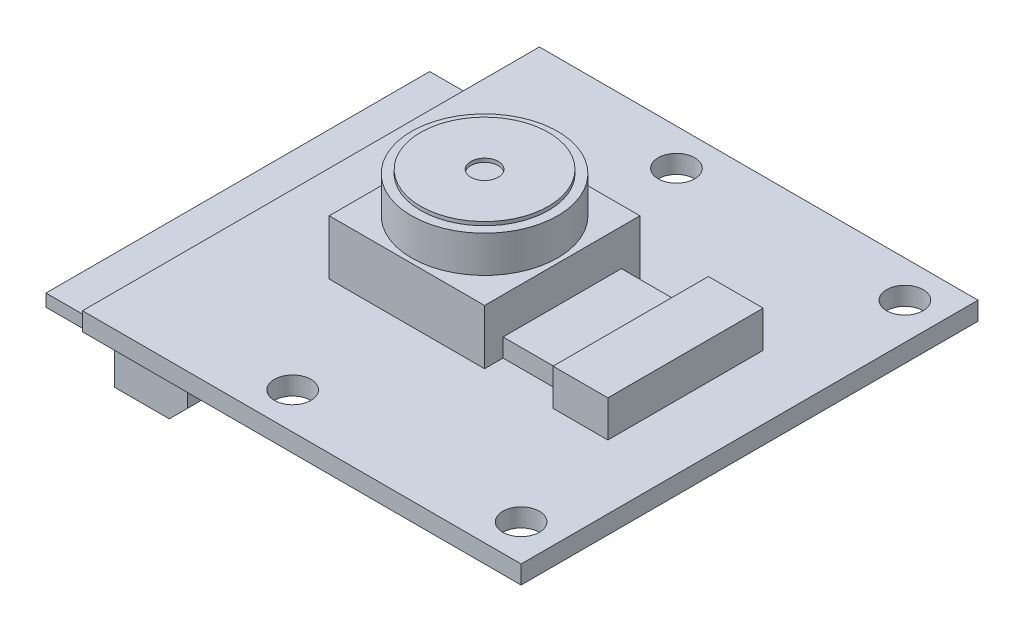
SolidWorks part; units mm, degrees
ref_plane "前视基准面" through (0, 0, 0) normal (0, 0, 1) x (1, 0, 0)
ref_plane "上视基准面" through (0, 0, 0) normal (0, 1, 0) x (1, 0, 0)
ref_plane "右视基准面" through (0, 0, 0) normal (1, 0, 0) x (0, 0, -1)
sketch "草图1" plane through (0, 0, 0) normal (0, 1, 0) x (1, 0, 0)
  line L1 (-12, 12.5) -> (12, 12.5)
  line L2 (-12, 12.5) -> (-12, -12.5)
  line L3 (-12, -12.5) -> (12, -12.5)
  line L4 (12, 12.5) -> (12, -12.5)
  line L5 (-12, 12.5) -> (12, -12.5) construction
  line L6 (-12, -12.5) -> (12, 12.5) construction
  point P0 (0, 0)
  dimension "D1" = 24
  dimension "D2" = 25
extrude "凸台-拉伸1" add sketch "草图1" along normal blind 1
sketch "草图2" plane through (0, 1, 0) normal (0, 1, 0) x (1, 0, 0)
  line L0 (-12, -12.5) -> (12, -12.5) construction
  line L1 (-6.75, -4.25) -> (1.75, -4.25)
  line L2 (-6.75, -4.25) -> (-6.75, 4.25)
  line L3 (-6.75, 4.25) -> (1.75, 4.25)
  line L4 (1.75, -4.25) -> (1.75, 4.25)
  line L5 (-6.75, -4.25) -> (1.75, 4.25) construction
  line L6 (-6.75, 4.25) -> (1.75, -4.25) construction
  line L9 (12, -12.5) -> (12, 12.5) construction
  point P0 (-2.5, 0)
  dimension "D1" = 12.5
  dimension "D2" = 14.5
  dimension "D3" = 8.5
  dimension "D4" = 8.5
extrude "凸台-拉伸2" add sketch "草图2" along normal blind 3
sketch "草图3" plane through (0, 4, 0) normal (0, 1, 0) x (1, 0, 0)
  circle A0 centre (-2.5, 0) radius 4
  dimension "D1" = 8
extrude "凸台-拉伸3" add sketch "草图3" along normal blind 2
sketch "草图4" plane through (0, 1, 0) normal (0, 1, 0) x (1, 0, 0)
  line L0 (12, -12.5) -> (12, 12.5) construction
  line L1 (5.5, -4.2542) -> (8.5, -4.2542)
  line L2 (5.5, -4.2542) -> (5.5, 4.2458)
  line L3 (5.5, 4.2458) -> (8.5, 4.2458)
  line L4 (8.5, -4.2542) -> (8.5, 4.2458)
  line L5 (5.5, -4.2542) -> (8.5, 4.2458) construction
  line L6 (5.5, 4.2458) -> (8.5, -4.2542) construction
  point P0 (7, -0.0042)
  dimension "D1" = 8.5
  dimension "D2" = 5
  dimension "D3" = 3
extrude "凸台-拉伸4" add sketch "草图4" along normal blind 2
sketch "草图5" plane through (0, 1, 0) normal (0, 1, 0) x (1, 0, 0)
  line L0 (1.75, -4.25) -> (1.75, 4.25) construction
  line L1 (1.75, 3.2381) -> (5.5, 3.2381)
  line L2 (1.75, 3.2381) -> (1.75, -3.2381)
  line L3 (1.75, -3.2381) -> (5.5, -3.2381)
  line L4 (5.5, 3.2381) -> (5.5, -3.2381)
  line L5 (5.5, 4.2458) -> (5.5, -4.2542) construction
extrude "凸台-拉伸5" add sketch "草图5" along normal blind 1
sketch "草图6" plane through (0, 0, 0) normal (0, 1, 0) x (1, 0, 0)
  line L0 (-12, -12.5) -> (12, -12.5) construction
  line L1 (-11, -11.75) -> (-7, -11.75)
  line L2 (-11, -11.75) -> (-11, 11.75)
  line L3 (-11, 11.75) -> (-7, 11.75)
  line L4 (-7, -11.75) -> (-7, 11.75)
  line L5 (-12, 12.5) -> (-12, -12.5) construction
  dimension "D1" = 23.5
  dimension "D2" = 0.75
  dimension "D3" = 4
  dimension "D4" = 1
extrude "凸台-拉伸6" add sketch "草图6" against normal blind 2.5
chamfer "倒角1" distance 1 angle 45 1 edges at (-7, -2.5, 0)
sketch "草图7" plane through (-11, 0, 0) normal (-1, 0, 0) x (0, 0, 1)
  line L1 (10.4968, -1.8365) -> (-10.4968, -1.8365)
  line L2 (10.4968, -1.8365) -> (10.4968, -1.1635)
  line L3 (10.4968, -1.1635) -> (-10.4968, -1.1635)
  line L4 (-10.4968, -1.8365) -> (-10.4968, -1.1635)
  line L5 (10.4968, -1.8365) -> (-10.4968, -1.1635) construction
  line L6 (10.4968, -1.1635) -> (-10.4968, -1.8365) construction
  point P0 (0, -1.5)
  dimension "D1" = 20.9936
  dimension "D2" = 0.673
extrude "凸台-拉伸7" add sketch "草图7" along normal blind 5
sketch "草图8" plane through (0, 1, 0) normal (0, 1, 0) x (1, 0, 0)
  line L0 (-12, -12.5) -> (12, -12.5) construction
  line L1 (12, -12.5) -> (12, 12.5) construction
  line L2 (12, 12.5) -> (-12, 12.5) construction
  circle A0 centre (10, -10.5) radius 1
  circle A1 centre (10, 10.5) radius 1
  circle A2 centre (-2.5, -10.5) radius 1
  circle A3 centre (-2.5, 10.5) radius 1
  dimension "D3" = 2
  dimension "D1" = 2
  dimension "D2" = 2
  dimension "D4" = 2
  dimension "D5" = 12.5
extrude "切除-拉伸1" cut sketch "草图8" against normal blind 1
sketch "草图9" plane through (0, 6, 0) normal (0, 1, 0) x (1, 0, 0)
  circle A0 centre (-2.5, 0) radius 3.5
  dimension "D1" = 7
extrude "凸台-拉伸8" add sketch "草图9" along normal blind 0.2
sketch "草图10" plane through (0, 6.2, 0) normal (0, 1, 0) x (1, 0, 0)
  circle A0 centre (-2.5, 0) radius 0.75
  dimension "D1" = 1.5
extrude "切除-拉伸2" cut sketch "草图10" against normal blind 0.2
